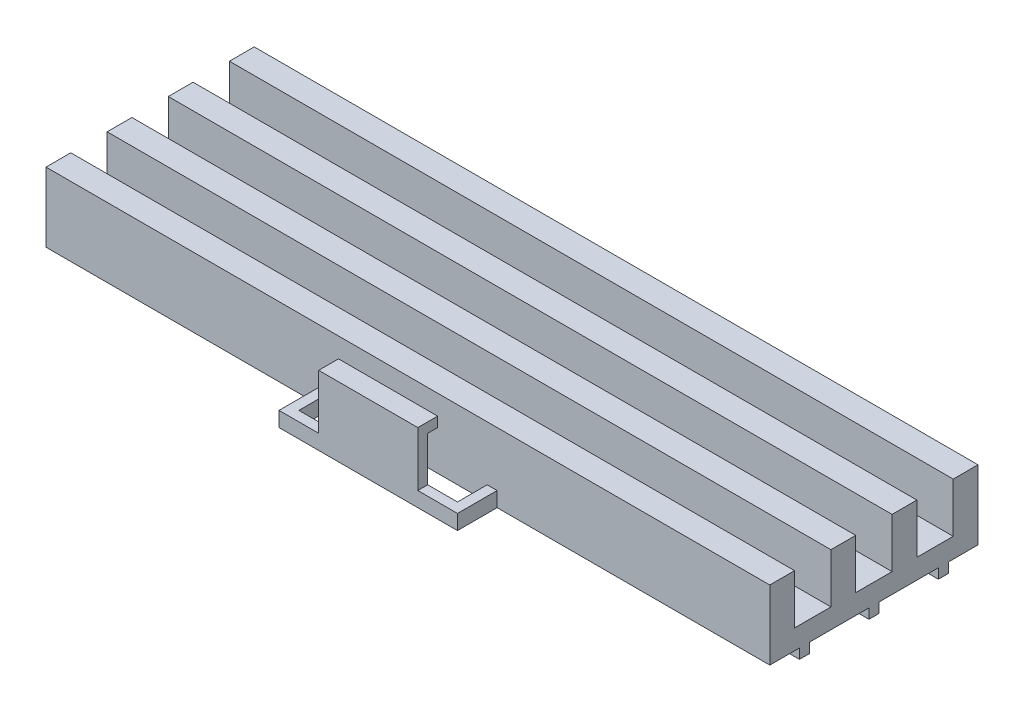
SolidWorks part; units mm, degrees
ref_plane "Front Plane" through (0, 0, 0) normal (0, 0, 1) x (1, 0, 0)
ref_plane "Top Plane" through (0, 0, 0) normal (0, 1, 0) x (1, 0, 0)
ref_plane "Right Plane" through (0, 0, 0) normal (1, 0, 0) x (0, 0, -1)
sketch "Sketch1" plane through (0, 0, 0) normal (1, 0, 0) x (0, 0, -1)
  line L0 (0, 0) -> (0, 19.1344) construction
  line L1 (0.5, 0) -> (-0.5, 0)
  line L2 (-0.5, 0) -> (-0.5, 1)
  line L3 (-0.5, 1) -> (-6.5, 1)
  line L4 (-6.5, 1) -> (-6.5, 0)
  line L5 (-6.5, 0) -> (-7.5, 0)
  line L6 (-7.5, 0) -> (-7.5, 1)
  line L7 (-7.5, 1) -> (-10.5, 1)
  line L8 (-10.5, 1) -> (-10.5, 8)
  line L9 (-10.5, 8) -> (-8, 8)
  line L10 (-8, 8) -> (-8, 3)
  line L11 (-8, 3) -> (-4.3333, 3)
  line L12 (-4.3333, 3) -> (-4.3333, 8)
  line L13 (-4.3333, 8) -> (-1.8333, 8)
  line L14 (-1.8333, 8) -> (-1.8333, 3)
  line L15 (-1.8333, 3) -> (1.8333, 3)
  line L16 (1.8333, 8) -> (1.8333, 3)
  line L17 (4.3333, 8) -> (1.8333, 8)
  line L18 (4.3333, 3) -> (4.3333, 8)
  line L19 (8, 3) -> (4.3333, 3)
  line L20 (8, 8) -> (8, 3)
  line L21 (10.5, 8) -> (8, 8)
  line L22 (10.5, 1) -> (10.5, 8)
  line L23 (7.5, 1) -> (10.5, 1)
  line L24 (7.5, 0) -> (7.5, 1)
  line L25 (6.5, 0) -> (7.5, 0)
  line L26 (6.5, 1) -> (6.5, 0)
  line L27 (0.5, 1) -> (6.5, 1)
  line L28 (0.5, 0) -> (0.5, 1)
  point P20 (0, 3)
  point P44 (7.5, 0.5)
  dimension "D1" = 21
  dimension "D2" = 15
  dimension "D3" = 1
  dimension "D4" = 7
  dimension "D5" = 1
  dimension "D6" = 2.5
  dimension "D7" = 5
extrude "Boss-Extrude1" add sketch "Sketch1" along normal mid plane 73 contours L18 L17 L16 L15 L14 L13 L12 L11 L10 L9 L8 L7 L6 L5 L4 L3 L2 L1 L28 L27 L26 L25 L24 L23 L22 L21 L20 L19
sketch "Sketch3" plane through (0, 1, 0) normal (0, 1, 0) x (1, 0, 0)
  line L0 (0, 0) -> (0, -17.5051) construction
  line L1 (-9, -10.5) -> (-9, -14.5)
  line L2 (36.5, -10.5) -> (-36.5, -10.5) construction
  line L3 (-9, -14.5) -> (9, -14.5)
  line L4 (9, -10.5) -> (9, -14.5)
  line L5 (36.5, 10.5) -> (-36.5, 10.5) construction
  point P9 (0, -14.5)
  dimension "D1" = 18
  dimension "D2" = 25
extrude "Extrude-Thin1" add sketch "Sketch3" along normal blind 1.5 thin contours L1 L3 L4 thin type one direction wall 1
sketch "Sketch4" plane through (0, 0, 0) normal (1, 0, 0) x (0, 0, -1)
  line L0 (-14.5, 2.5) -> (-14.5, 8)
  line L1 (-14.5, 8) -> (-12.5, 8)
  line L3 (-10.5, 1) -> (-14.5, 1) construction
  dimension "D1" = 2
  dimension "D2" = 7
extrude "Extrude-Thin2" add sketch "Sketch4" along normal mid plane 10 thin contours L0 L1
